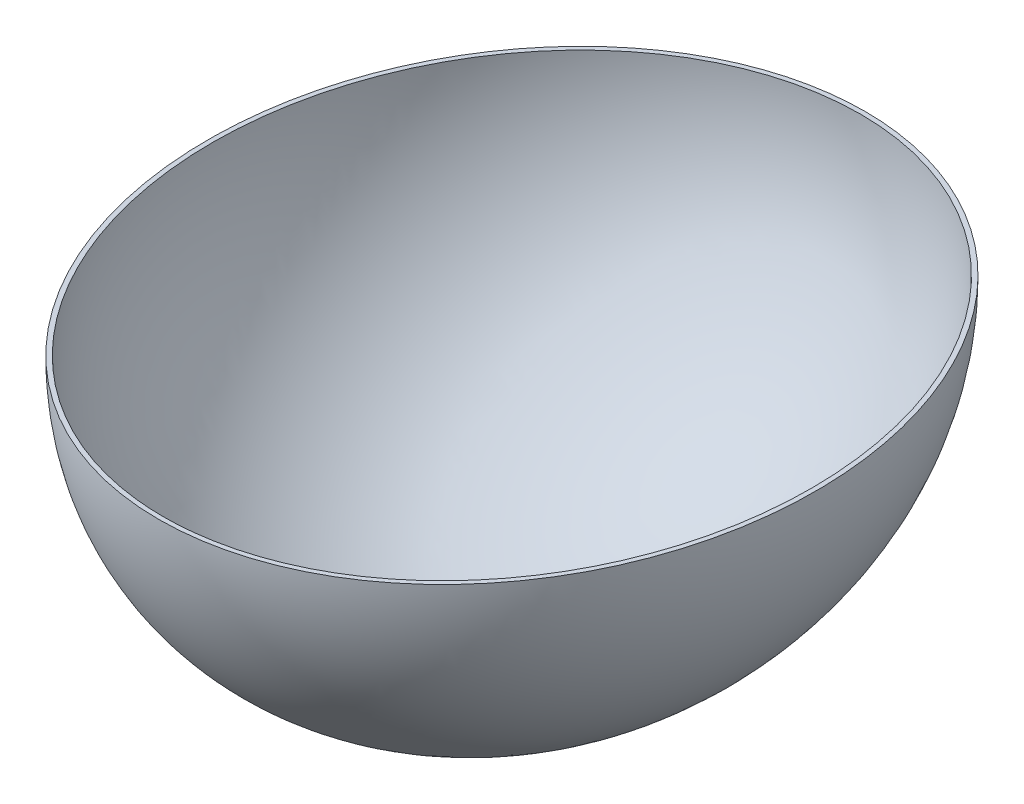
SolidWorks part; units mm, degrees
ref_plane "Front Plane" through (0, 0, 0) normal (0, 0, 1) x (1, 0, 0)
ref_plane "Top Plane" through (0, 0, 0) normal (0, 1, 0) x (1, 0, 0)
ref_plane "Right Plane" through (0, 0, 0) normal (1, 0, 0) x (0, 0, -1)
sketch "Sketch1" plane through (0, 0, 0) normal (0, 1, 0) x (1, 0, 0)
  line L0 (0, 0) -> (0, 50000) construction
  line L1 (0, 230) -> (0, 227)
  line L2 (0, -227) -> (0, -230)
  ellipse E0 centre (0, 0) end of major axis (0, 230) minor radius 198 (0, -230) -> (0, 230) ccw
  spline S0 degree 1 poles (0, -227) (0, 227) knots 0 0 1 1 construction
  spline S1 degree 3 poles (0, -227) (12.7334, -227) (38.1916, -224.0875) (74.9443, -211.1396) (108.8546, -190.0878) (138.618, -161.7178) (163.0748, -127.1048) (181.266, -87.5749) (192.4758, -44.6529) (196.2621, 0) (192.4758, 44.6529) (181.266, 87.5749) (163.0748, 127.1048) (138.618, 161.7178) (108.8546, 190.0878) (74.9443, 211.1396) (38.1916, 224.0875) (12.7334, 227) (0, 227) knots -3.141593 -3.141593 -3.141593 -3.141593 -2.945243 -2.748894 -2.552544 -2.356194 -2.159845 -1.963495 -1.767146 -1.570796 -1.374447 -1.178097 -0.981748 -0.785398 -0.589049 -0.392699 -0.19635 0 0 0 0
  dimension "D1" = 3
revolve "Revolve1" add sketch "Sketch1" angle 180 about L0
